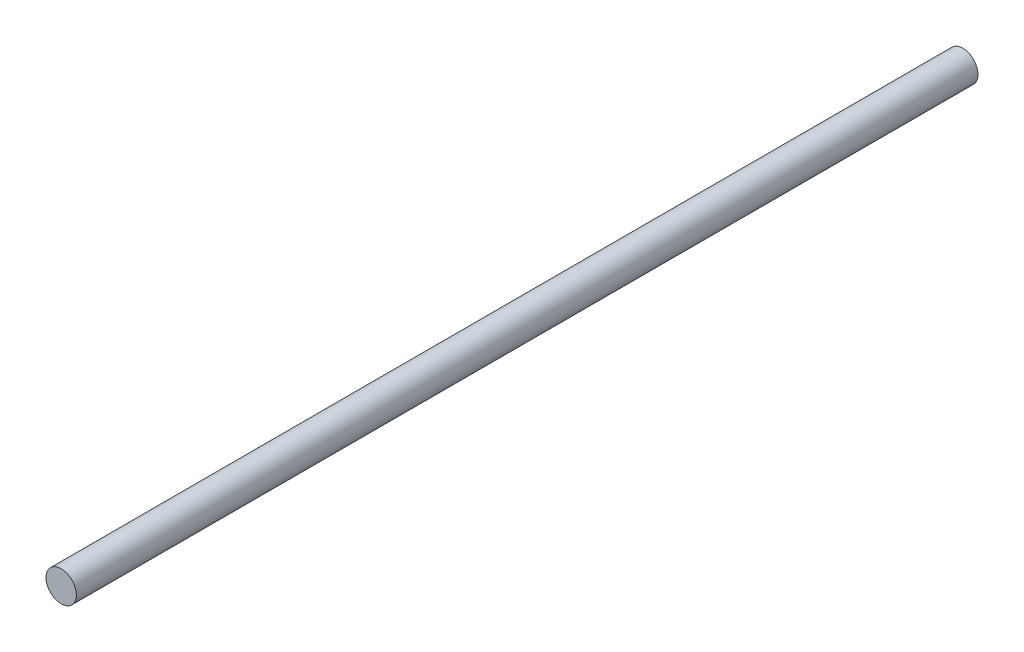
SolidWorks part; units mm, degrees
ref_plane "Front Plane" through (0, 0, 0) normal (0, 0, 1) x (1, 0, 0)
ref_plane "Top Plane" through (0, 0, 0) normal (0, 1, 0) x (1, 0, 0)
ref_plane "Right Plane" through (0, 0, 0) normal (1, 0, 0) x (0, 0, -1)
sketch "Sketch1" plane through (0, 0, 0) normal (0, 0, 1) x (1, 0, 0)
  circle A0 centre (0, 0) radius 1.5
  dimension "D1" = 3
extrude "Boss-Extrude1" add sketch "Sketch1" along normal blind 89
